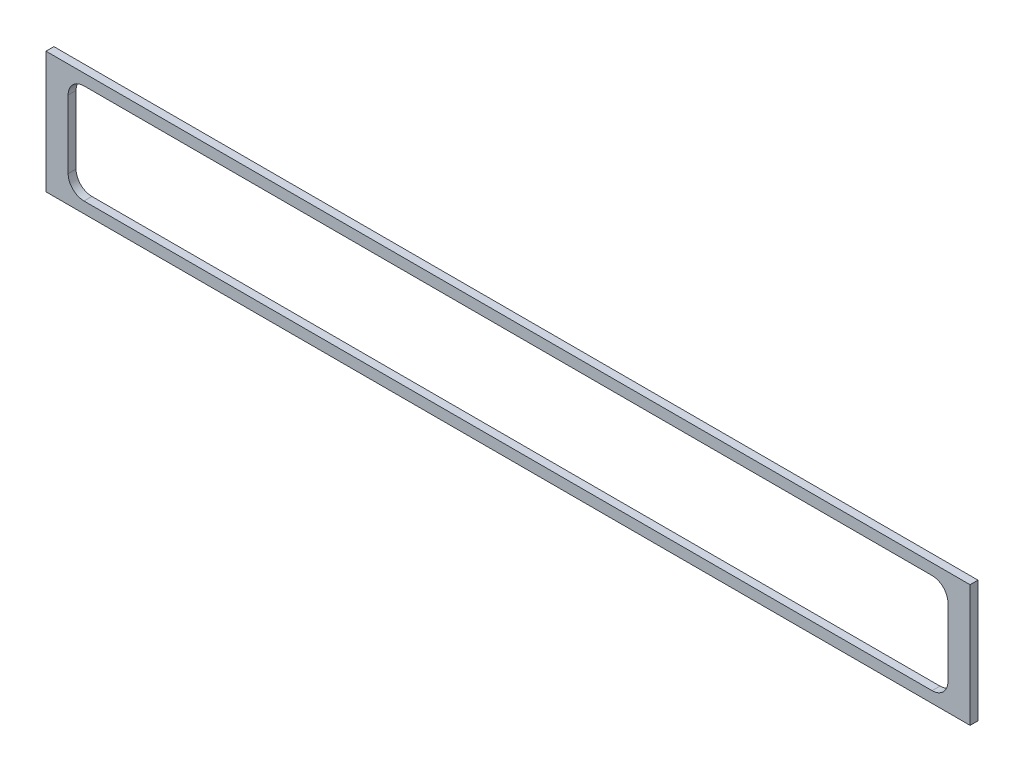
SolidWorks part; units mm, degrees
ref_plane "Płaszczyzna przednia" through (0, 0, 0) normal (0, 0, 1) x (1, 0, 0)
ref_plane "Płaszczyzna górna" through (0, 0, 0) normal (0, 1, 0) x (1, 0, 0)
ref_plane "Płaszczyzna prawa" through (0, 0, 0) normal (1, 0, 0) x (0, 0, -1)
sketch "Szkic1" plane through (0, 0, 0) normal (0, 0, 1) x (1, 0, 0)
  line L1 (-275.1965, 118.2584) -> (308.8035, 118.2584)
  line L2 (-275.1965, 118.2584) -> (-275.1965, 41.2584)
  line L3 (-275.1965, 41.2584) -> (308.8035, 41.2584)
  line L4 (308.8035, 118.2584) -> (308.8035, 41.2584)
  dimension "D1" = 584
  dimension "D2" = 77
extrude "Dodanie-wyciągnięcie1" add sketch "Szkic1" along normal blind 5
sketch "Szkic2" plane through (0, 0, 5) normal (0, 0, 1) x (1, 0, 0)
  line L0 (-275.1965, 118.2584) -> (-275.1965, 41.2584) construction
  line L1 (-251.1965, 111.2584) -> (284.8035, 111.2584)
  line L2 (-261.1965, 101.2584) -> (-261.1965, 58.2584)
  line L3 (-251.1965, 48.2584) -> (284.8035, 48.2584)
  line L4 (294.8035, 101.2584) -> (294.8035, 58.2584)
  line L5 (308.8035, 41.2584) -> (308.8035, 118.2584) construction
  line L6 (308.8035, 118.2584) -> (-275.1965, 118.2584) construction
  line L7 (-275.1965, 41.2584) -> (308.8035, 41.2584) construction
  arc A0 (284.8035, 111.2584) -> (294.8035, 101.2584) centre (284.8035, 101.2584) cw
  arc A1 (294.8035, 58.2584) -> (284.8035, 48.2584) centre (284.8035, 58.2584) cw
  arc A2 (-261.1965, 58.2584) -> (-251.1965, 48.2584) centre (-251.1965, 58.2584) ccw
  arc A3 (-261.1965, 101.2584) -> (-251.1965, 111.2584) centre (-251.1965, 101.2584) cw
  dimension "D5" = 10
  dimension "D1" = 14
  dimension "D2" = 14
  dimension "D3" = 7
  dimension "D4" = 7
extrude "Wytnij-wyciągnięcie1" cut sketch "Szkic2" against normal blind 5
